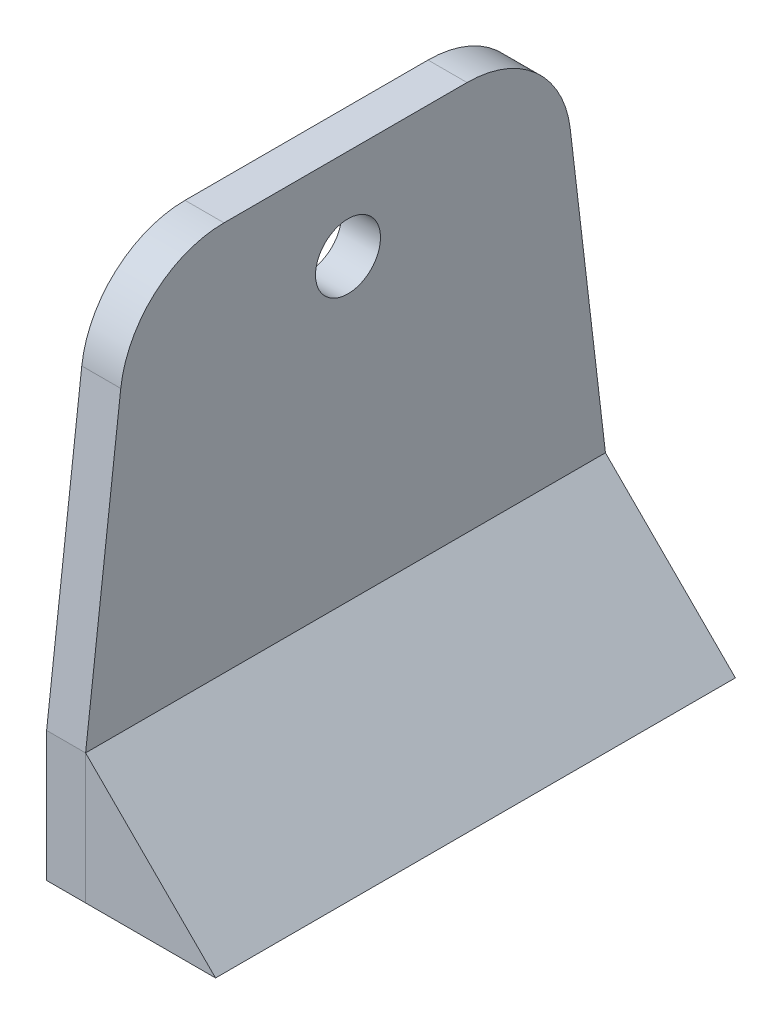
SolidWorks part; units mm, degrees
ref_plane "Front Plane" through (0, 0, 0) normal (0, 0, 1) x (1, 0, 0)
ref_plane "Top Plane" through (0, 0, 0) normal (0, 1, 0) x (1, 0, 0)
ref_plane "Right Plane" through (0, 0, 0) normal (1, 0, 0) x (0, 0, -1)
sketch "Sketch2" plane through (-18.65, 0, 0) normal (-1, 0, 0) x (0, 0, 1)
  line L0 (20, 10) -> (20, 0) construction
  line L1 (-20, 10) -> (-20, 0) construction
  line L2 (20, 0) -> (-20, 0) construction
  line L3 (20, 10) -> (20, 0)
  line L4 (-20, 10) -> (-20, 0)
  line L5 (20, 0) -> (-20, 0)
  line L6 (-20, 10) -> (-12.9587, 69.7028) construction
  line L7 (12.9587, 69.7028) -> (20, 10) construction
  line L8 (-20, 10) -> (-17.2948, 32.937)
  line L9 (17.2948, 32.937) -> (20, 10)
  line L10 (-9.3499, 40) -> (9.3499, 40)
  line L13 (0, 0) -> (0, 40) construction
  circle A0 centre (-0.1915, 33) radius 2.5
  arc A1 (-17.2948, 32.937) -> (-9.3499, 40) centre (-9.3499, 32) cw
  arc A2 (17.2948, 32.937) -> (9.3499, 40) centre (9.3499, 32) ccw
  point P16 (-16.4618, 40)
  point P19 (16.4618, 40)
  dimension "D1" = 5
  dimension "D3" = 8
  dimension "D2" = 40
extrude "Boss-Extrude1" add sketch "Sketch2" along normal blind 3
sketch "Sketch3" plane through (0, 0, 0) normal (0, 0, 1) x (1, 0, 0)
  line L0 (10, 0) -> (20, 0) construction
  line L7 (-18.65, 10) -> (-8.65, 0)
  line L8 (-8.65, 0) -> (-18.65, 0)
  line L9 (-18.65, 10) -> (-18.65, 0)
extrude "Boss-Extrude2" add sketch "Sketch3" along normal mid plane 40 separate body
